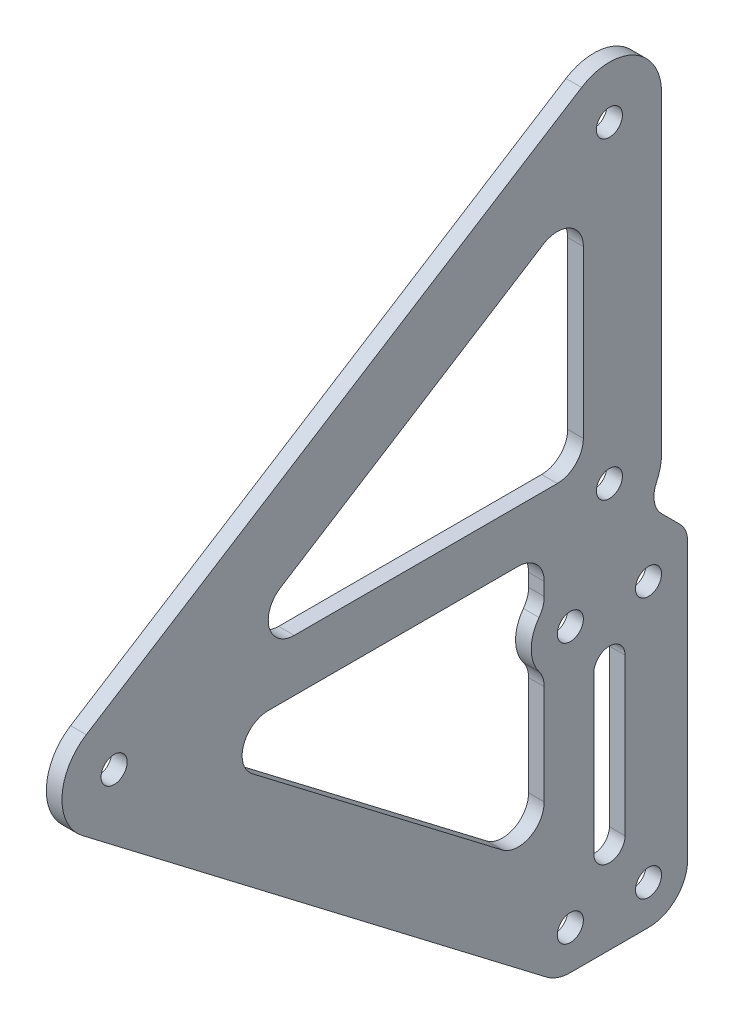
SolidWorks part; units mm, degrees
material "AISI 304"
ref_plane "前视基准面" through (0, 0, 0) normal (0, 0, 1) x (1, 0, 0)
ref_plane "上视基准面" through (0, 0, 0) normal (0, 1, 0) x (1, 0, 0)
ref_plane "右视基准面" through (0, 0, 0) normal (1, 0, 0) x (0, 0, -1)
sketch "草图1" plane through (0, 0, 0) normal (1, 0, 0) x (0, 0, -1)
  line L0 (0, 0) -> (87.5, 0) construction
  line L1 (95, 0) -> (95, 60) construction
  line L2 (-5.3399, 8.4549) -> (89.6601, 68.4549)
  line L3 (105, 60) -> (105, 0)
  line L4 (95, 0) -> (95, -70) construction
  line L5 (87.5, 0) -> (87.5, -66.8538) construction
  line L6 (102.5, 0) -> (102.5, -70) construction
  line L7 (124.3191, -20) -> (23.6281, -20) construction
  line L8 (95, 60) -> (0, 0) construction
  line L9 (110, -17.0711) -> (110, -70)
  line L10 (87.5, -77.5) -> (102.5, -77.5)
  line L11 (-6.0712, -7.9461) -> (82.9466, -75.9596)
  line L12 (105, -10) -> (108.5355, -13.5355)
  line L13 (82.33, 46.0842) -> (31.8902, 14.2274)
  line L14 (34.5602, 5) -> (85, 5)
  line L15 (90, 10) -> (90, 41.8567)
  line L16 (17.2801, 5) -> (90, 5) construction
  line L17 (90, 5) -> (90, 50.9284) construction
  line L18 (90, 50.9284) -> (17.2801, 5) construction
  line L19 (0, 0) -> (87.5, -66.8538) construction
  line L20 (92.5, 0) -> (95, 0) construction
  line L21 (87.5, -67.5) -> (87.5, -70) construction
  line L22 (0, 0) -> (95, 0) construction
  line L23 (29.5595, -5) -> (77.5, -5)
  line L24 (87.5, 0) -> (87.5, -70) construction
  line L25 (82.5, -10) -> (82.5, -12.5)
  line L26 (26.5239, -13.9731) -> (74.4644, -50.6017)
  line L27 (14.7798, -5) -> (82.5, -56.7412) construction
  line L28 (82.5, -5) -> (82.5, -56.7412) construction
  line L29 (14.7798, -5) -> (82.5, -5) construction
  line L30 (82.5, -27.5) -> (82.5, -46.6286)
  line L31 (95, -30) -> (95, -60) construction
  line L32 (98, -30) -> (98, -60)
  line L33 (92, -30) -> (92, -60)
  circle A0 centre (0, 0) radius 2.5
  arc A1 (-5.3399, 8.4549) -> (-6.0712, -7.9461) centre (0, 0) ccw
  circle A2 centre (95, 0) radius 2.5
  arc A3 (104.0237, -4.3096) -> (105, 0) centre (95, 0) ccw
  circle A4 centre (95, 60) radius 2.5
  arc A5 (105, 60) -> (89.6601, 68.4549) centre (95, 60) ccw
  circle A6 centre (87.5, -20) radius 2.5
  circle A7 centre (102.5, -20) radius 2.5
  circle A8 centre (87.5, -70) radius 2.5
  circle A9 centre (102.5, -70) radius 2.5
  arc A10 (102.5, -77.5) -> (110, -70) centre (102.5, -70) ccw
  arc A11 (82.9466, -75.9596) -> (87.5, -77.5) centre (87.5, -70) ccw
  arc A12 (110, -17.0711) -> (108.5355, -13.5355) centre (105, -17.0711) ccw
  arc A13 (105, -10) -> (104.0237, -4.3096) centre (108.5355, -6.4645) cw
  arc A14 (85, 5) -> (90, 10) centre (85, 10) ccw
  arc A15 (90, 41.8567) -> (82.33, 46.0842) centre (85, 41.8567) ccw
  arc A16 (34.5602, 5) -> (31.8902, 14.2274) centre (34.5602, 10) cw
  arc A17 (74.4644, -50.6017) -> (82.5, -46.6286) centre (77.5, -46.6286) ccw
  arc A18 (82.5, -10) -> (77.5, -5) centre (77.5, -10) ccw
  arc A19 (26.5239, -13.9731) -> (29.5595, -5) centre (29.5595, -10) cw
  arc A20 (81.5, -15.5) -> (81.5, -24.5) centre (87.5, -20) ccw
  arc A21 (82.5, -27.5) -> (81.5, -24.5) centre (77.5, -27.5) ccw
  arc A22 (81.5, -15.5) -> (82.5, -12.5) centre (77.5, -12.5) ccw
  arc A23 (98, -30) -> (92, -30) centre (95, -30) ccw
  arc A24 (92, -60) -> (98, -60) centre (95, -60) ccw
  point P35 (110, -15)
  point P38 (102.0711, -7.0711)
  point P68 (82.5, -25.5902)
  point P73 (95, -45)
  dimension "D1" = 5
  dimension "D2" = 20
  dimension "D4" = 5
  dimension "D5" = 20
  dimension "D7" = 5
  dimension "D8" = 20
  dimension "D13" = 5
  dimension "D14" = 5
  dimension "D15" = 5
  dimension "D16" = 5
  dimension "D20" = 5
  dimension "D22" = 5
  dimension "D24" = 5
  dimension "D25" = 15
  dimension "D26" = 5
  dimension "D29" = 3
  dimension "D3" = 95
  dimension "D6" = 60
  dimension "D9" = 70
  dimension "D12" = 20
  dimension "D17" = 45
  dimension "D18" = 15
  dimension "D19" = 11.2132
  dimension "D27" = 10
  dimension "D28" = 10
  dimension "D10" = 7.5
  dimension "D11" = 7.5
  dimension "D21" = 5
  dimension "D23" = 5
extrude "凸台-拉伸1" add sketch "草图1" along normal blind 3
